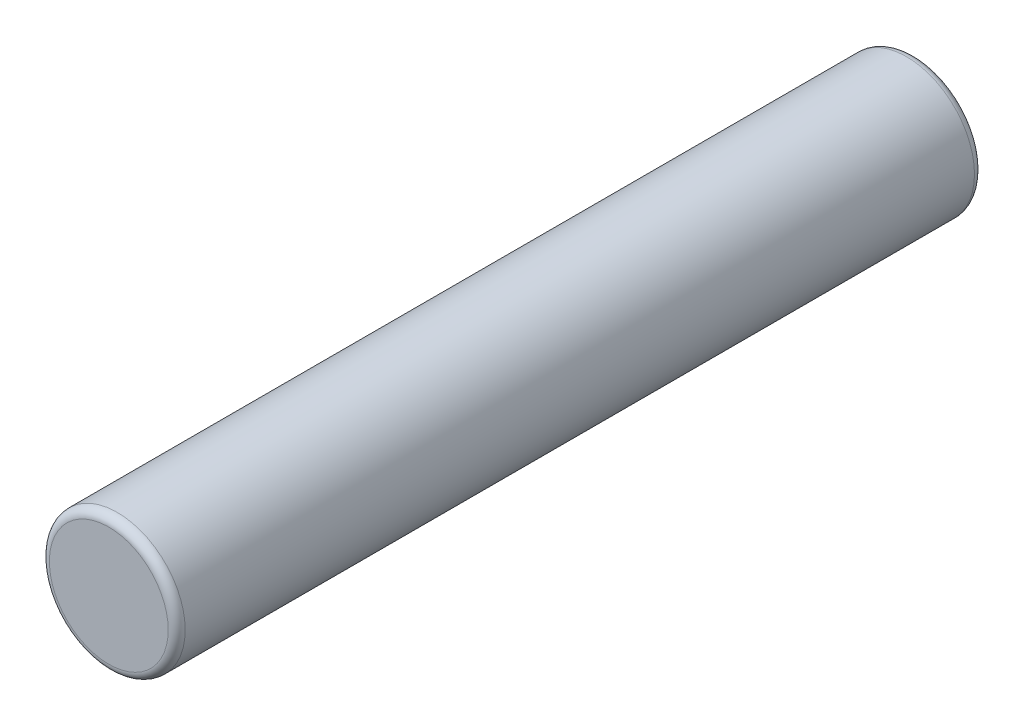
SolidWorks part; units mm, degrees
ref_plane "Front Plane" through (0, 0, 0) normal (0, 0, 1) x (1, 0, 0)
ref_plane "Top Plane" through (0, 0, 0) normal (0, 1, 0) x (1, 0, 0)
ref_plane "Right Plane" through (0, 0, 0) normal (1, 0, 0) x (0, 0, -1)
sketch "Sketch1" plane through (0, 0, 0) normal (0, 0, 1) x (1, 0, 0)
  circle A0 centre (0, 0) radius 0.8
  dimension "D1" = 1.6
extrude "Boss-Extrude1" add sketch "Sketch1" along normal blind 9.5
fillet "Fillet1" radius 0.1 2 edges at (0.8, 0, 9.5) (0.8, 0, 0)
